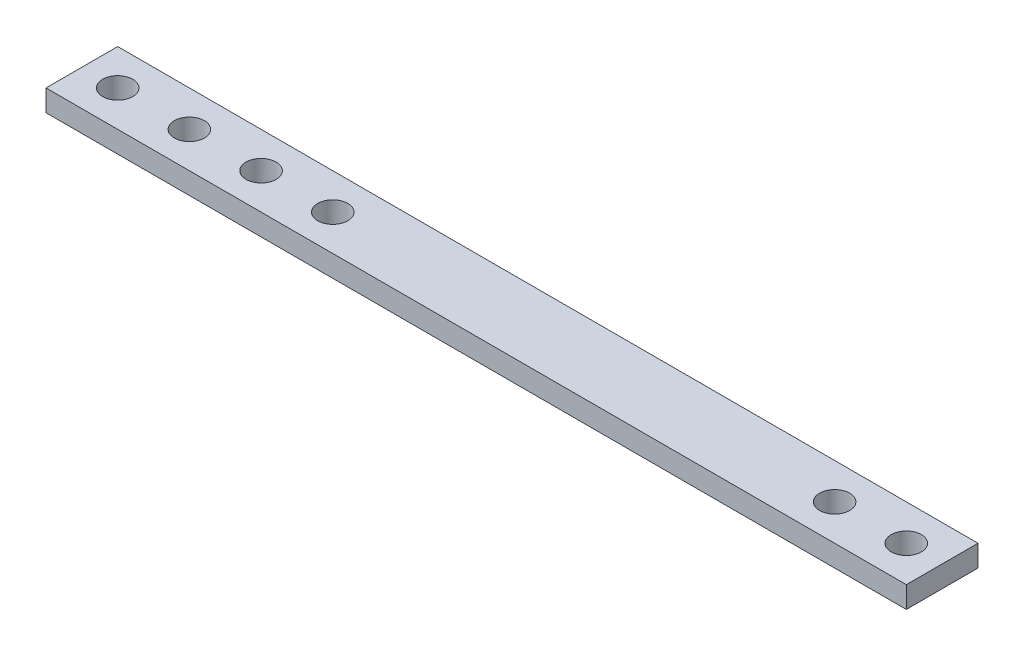
SolidWorks part; units mm, degrees
ref_plane "Alzado" through (0, 0, 0) normal (0, 0, 1) x (1, 0, 0)
ref_plane "Planta" through (0, 0, 0) normal (0, 1, 0) x (1, 0, 0)
ref_plane "Vista lateral" through (0, 0, 0) normal (1, 0, 0) x (0, 0, -1)
sketch "Croquis1" plane through (0, 0, 0) normal (0, 1, 0) x (1, 0, 0)
  line L1 (-60, -5) -> (60, -5)
  line L2 (-60, -5) -> (-60, 5)
  line L3 (-60, 5) -> (60, 5)
  line L4 (60, -5) -> (60, 5)
  line L5 (0, 5) -> (0, -5) construction
  line L6 (-60, 0) -> (60, 0) construction
  circle A0 centre (-55, 0) radius 2.1
  circle A1 centre (-45, 0) radius 2.1
  circle A2 centre (-35, 0) radius 2.1
  circle A3 centre (-25, 0) radius 2.1
  point P0 (0, 0)
  dimension "D3" = 5
  dimension "D4" = 4.2
  dimension "D1" = 10
  dimension "D2" = 120
  dimension "D5" = 4
extrude "Saliente-Extruir1" add sketch "Croquis1" along normal blind 3
sketch "Croquis2" plane through (0, 3, 0) normal (0, 1, 0) x (1, 0, 0)
  line L0 (60, -5) -> (60, 5) construction
  circle A0 centre (55, 0) radius 2.1
  circle A1 centre (45, 0) radius 2.1
  dimension "D1" = 5
  dimension "D2" = 4.2
  dimension "D3" = 2
extrude "Cortar-Extruir1" cut sketch "Croquis2" against normal blind 3
